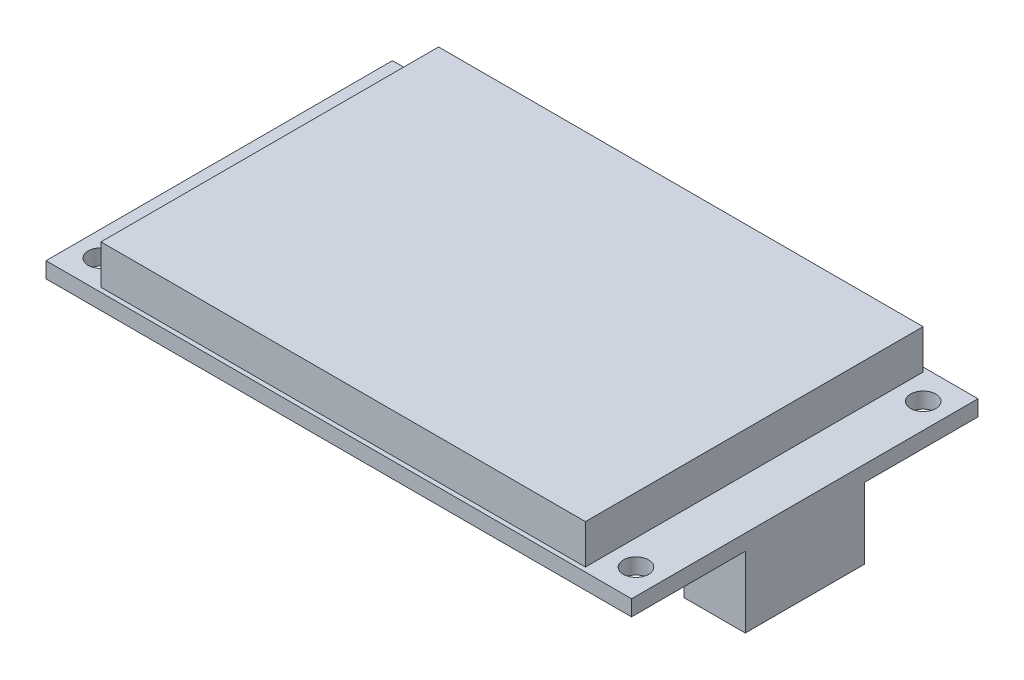
SolidWorks part; units mm, degrees
material "C-玻璃纤维"
ref_plane "前视基准面" through (0, 0, 0) normal (0, 0, 1) x (1, 0, 0)
ref_plane "上视基准面" through (0, 0, 0) normal (0, 1, 0) x (1, 0, 0)
ref_plane "右视基准面" through (0, 0, 0) normal (1, 0, 0) x (0, 0, -1)
other "Configuration Table"
sketch "草图1" plane through (0, 0, 0) normal (0, 1, 0) x (1, 0, 0)
  line L0 (0, 0) -> (42.983, 0) construction
  line L1 (-37.2, -22.01) -> (37.2, -22.01)
  line L2 (-37.2, -22.01) -> (-37.2, 22.01)
  line L3 (-37.2, 22.01) -> (37.2, 22.01)
  line L4 (37.2, -22.01) -> (37.2, 22.01)
  line L5 (-37.2, -22.01) -> (37.2, 22.01) construction
  line L6 (-37.2, 22.01) -> (37.2, -22.01) construction
  line L7 (0, 0) -> (0, 26.1623) construction
  circle A0 centre (-34, 18.25) radius 1.6
  circle A1 centre (34, 18.25) radius 1.6
  circle A2 centre (34, -18.25) radius 1.6
  circle A3 centre (-34, -18.25) radius 1.6
  point P0 (0, 0)
  dimension "D3" = 3.2
  dimension "D4" = 68
  dimension "D5" = 36.5
  dimension "D1" = 74.4
  dimension "D2" = 44.02
extrude "凸台-拉伸1" add sketch "草图1" along normal blind 2
sketch "草图2" plane through (0, 2, 0) normal (0, 1, 0) x (1, 0, 0)
  line L1 (-30.78, -21.45) -> (30.78, -21.45)
  line L2 (-30.78, -21.45) -> (-30.78, 21.45)
  line L3 (-30.78, 21.45) -> (30.78, 21.45)
  line L4 (30.78, -21.45) -> (30.78, 21.45)
  line L5 (-30.78, -21.45) -> (30.78, 21.45) construction
  line L6 (-30.78, 21.45) -> (30.78, -21.45) construction
  point P0 (0, 0)
  dimension "D1" = 61.56
  dimension "D2" = 42.9
extrude "凸台-拉伸2" add sketch "草图2" along normal blind 5
sketch "草图3" plane through (0, 0, 0) normal (0, -1, 0) x (1, 0, 0)
  line L0 (37.2, 22.01) -> (37.2, -22.01) construction
  line L1 (29.4, -7.56) -> (37.2, -7.56)
  line L2 (29.4, -7.56) -> (29.4, 7.56)
  line L3 (29.4, 7.56) -> (37.2, 7.56)
  line L4 (37.2, -7.56) -> (37.2, 7.56)
  line L5 (29.4, -7.56) -> (37.2, 7.56) construction
  line L6 (29.4, 7.56) -> (37.2, -7.56) construction
  point P0 (33.3, 0)
  dimension "D1" = 15.12
  dimension "D2" = 7.8
  dimension "D3" = 0
extrude "凸台-拉伸3" add sketch "草图3" along normal blind 9
